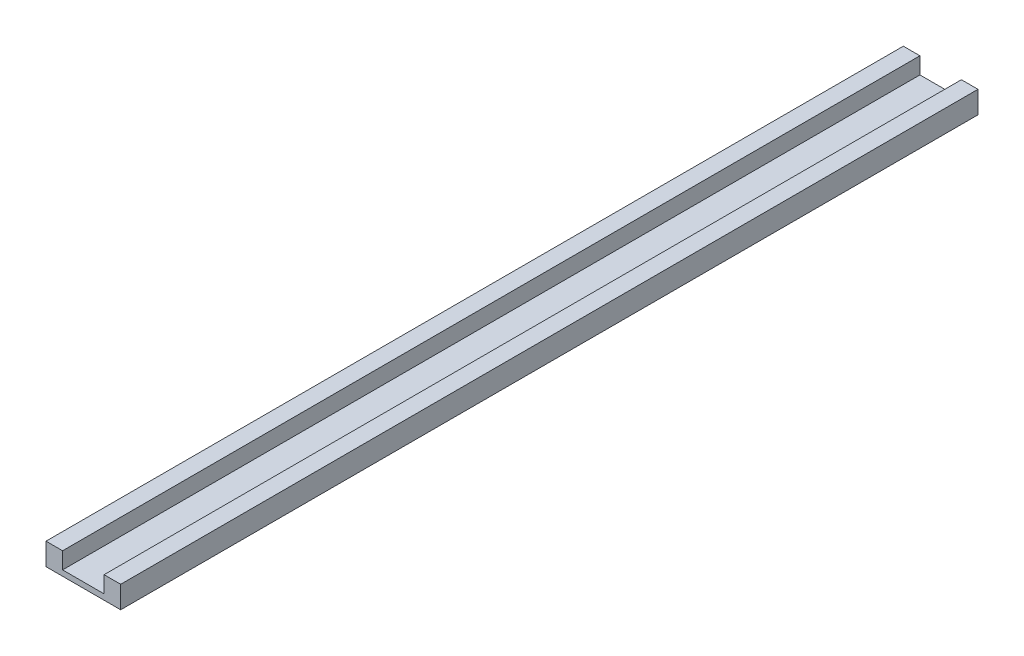
SolidWorks part; units mm, degrees
ref_plane "Plan de face" through (0, 0, 0) normal (0, 0, 1) x (1, 0, 0)
ref_plane "Plan de dessus" through (0, 0, 0) normal (0, 1, 0) x (1, 0, 0)
ref_plane "Plan de droite" through (0, 0, 0) normal (1, 0, 0) x (0, 0, -1)
sketch "Esquisse1" plane through (0, 0, 0) normal (0, 0, 1) x (1, 0, 0)
  line L1 (-13.5, 4) -> (13.5, 4)
  line L2 (-13.5, 4) -> (-13.5, -4)
  line L3 (-13.5, -4) -> (13.5, -4)
  line L4 (13.5, 4) -> (13.5, -4)
  line L5 (-13.5, 4) -> (13.5, -4) construction
  line L6 (-13.5, -4) -> (13.5, 4) construction
  line L7 (-7.5, 4) -> (7.5, 4)
  line L8 (-7.5, 4) -> (-7.5, -2)
  line L9 (-7.5, -2) -> (7.5, -2)
  line L10 (7.5, 4) -> (7.5, -2)
  point P0 (0, 0)
  dimension "D1" = 27
  dimension "D2" = 8
  dimension "D3" = 6
  dimension "D4" = 15
  dimension "D5" = 6
extrude "Boss.-Extru.1" add sketch "Esquisse1" along normal blind 350 contours L1 L10 L9 L8 L2 L3 L4
sketch "Sketch1" plane through (0, 0, 0) normal (0, 0, -1) x (-1, 0, 0)
  line L8 (-7.5, 4) -> (-13.5, 4)
  line L9 (-13.5, 4) -> (-13.5, -4)
  line L10 (-13.5, -4) -> (13.5, -4)
  line L11 (13.5, -4) -> (13.5, 4)
  line L12 (13.5, 4) -> (7.5, 4)
  line L13 (7.5, 4) -> (7.5, -2)
  line L14 (7.5, -2) -> (-7.5, -2)
  line L15 (-7.5, -2) -> (-7.5, 4)
  line L16 (-7.5, 4) -> (-13.5, 4)
  line L17 (-13.5, 4) -> (-13.5, -4)
  line L18 (-13.5, -4) -> (13.5, -4)
  line L19 (13.5, -4) -> (13.5, 4)
  line L20 (13.5, 4) -> (7.5, 4)
  line L21 (7.5, 4) -> (7.5, -2)
  line L22 (7.5, -2) -> (-7.5, -2)
  line L23 (-7.5, -2) -> (-7.5, 4)
  dimension "D1" = 0
extrude "Cut-Extrude1" cut sketch "Sketch1" against normal blind 40
